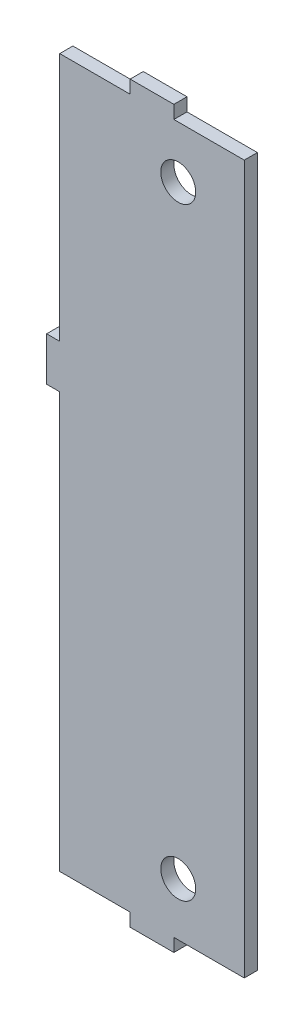
SolidWorks part; units mm, degrees
ref_plane "Front Plane" through (0, 0, 0) normal (0, 0, 1) x (1, 0, 0)
ref_plane "Top Plane" through (0, 0, 0) normal (0, 1, 0) x (1, 0, 0)
ref_plane "Right Plane" through (0, 0, 0) normal (1, 0, 0) x (0, 0, -1)
sketch "Sketch1" plane through (0, 0, 0) normal (0, 0, 1) x (1, 0, 0)
  line L16 (-5, 0) -> (5, 0)
  line L25 (-21.1, -3) -> (-21.1, -60)
  line L27 (-5, 0) -> (-5, -3)
  line L28 (5, 0) -> (5, -3)
  line L30 (-21.1, -60) -> (-24.1, -60)
  line L35 (5, -3) -> (21.1, -3)
  line L36 (-5, -3) -> (-21.1, -3)
  line L37 (-24.1, -60) -> (-24.1, -70)
  line L39 (-24.1, -70) -> (-21.1, -70)
  line L40 (-21.1, -70) -> (-21.1, -165)
  line L41 (-21.1, -165) -> (-5, -165)
  line L43 (-5, -165) -> (-5, -168)
  line L44 (-5, -168) -> (5, -168)
  line L45 (5, -168) -> (5, -165)
  line L46 (5, -165) -> (21.1, -165)
  line L47 (21.1, -3) -> (21.1, -165)
  point P3 (0, 0)
  dimension "D1" = 10
  dimension "D2" = 3
  dimension "D3" = 16.1
  dimension "D4" = 16.1
  dimension "D5" = 3
  dimension "D6" = 57
  dimension "D7" = 3
  dimension "D8" = 95
  dimension "D9" = 3
  dimension "D10" = 10
  dimension "D11" = 16.1
  dimension "D12" = 3
  dimension "D13" = 10
  dimension "D14" = 3
  dimension "D15" = 16.1
extrude "Boss-Extrude1" add sketch "Sketch1" along normal mid plane 3
sketch "Sketch2" plane through (0, 0, 1.5) normal (0, 0, 1) x (1, 0, 0)
  line L0 (21.1, -3) -> (6, -3) construction
  line L2 (6, -14.9) -> (6, -3) construction
  line L3 (-24.1, -60) -> (-24.1, -70) construction
  line L5 (6, -14.9) -> (6, -152.9) construction
  point P10 (6, -14.9)
  point P12 (6, -152.9)
  dimension "D1" = 15.1
  dimension "D2" = 11.9
  dimension "D4" = 30.1
  dimension "D5" = 138
hole_wizard "Ø8.0 (8) Diameter Hole1" positions "Sketch5" profile "Sketch6" hole size "Ø8.0" standard "AS" end condition through all
sketch "Sketch5" plane through (0, 0, 1.5) normal (0, 0, 1) x (1, 0, 0)
  point P0 (6, -14.9)
  point P3 (6, -152.9)
sketch "Sketch6" plane through (6, -14.9, 1.5) normal (1, 0, 0) x (0, -1, 0)
  line L0 (0, 0) -> (0, 3)
  line L1 (0, 3) -> (4, 3)
  line L2 (4, 3) -> (4, 0)
  line L5 (4, 0) -> (0, 0)
  line L11 (0, -6.35) -> (0, 107.95) construction
  dimension "Thru Hole Dia." = 8
  dimension "Thru Hole Depth" = 3
